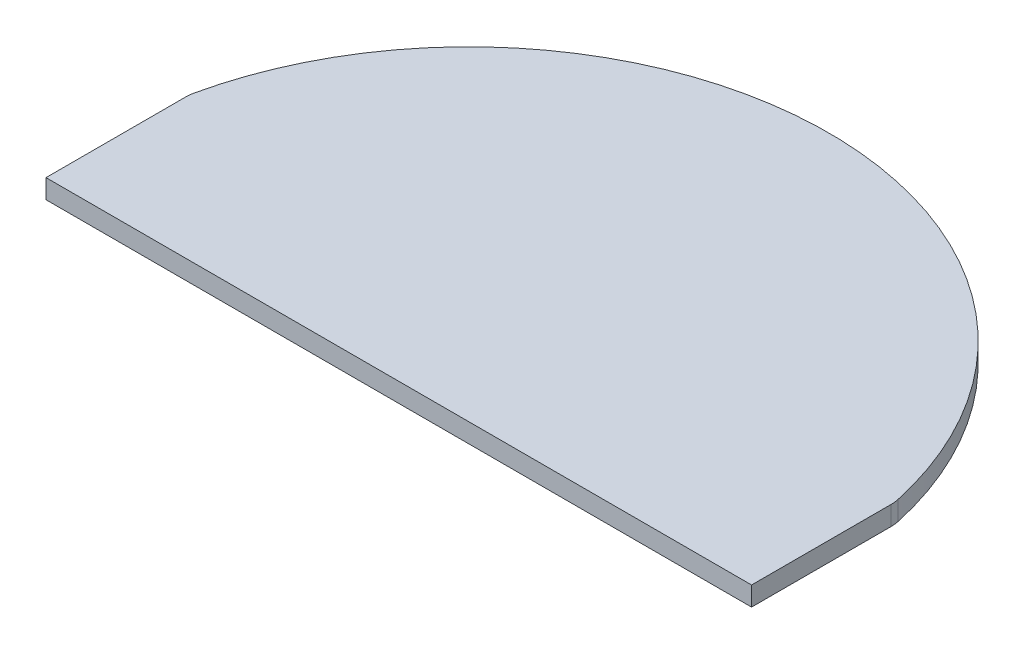
SolidWorks part; units mm, degrees
ref_plane "Front Plane" through (0, 0, 0) normal (0, 0, 1) x (1, 0, 0)
ref_plane "Top Plane" through (0, 0, 0) normal (0, 1, 0) x (1, 0, 0)
ref_plane "Right Plane" through (0, 0, 0) normal (1, 0, 0) x (0, 0, -1)
sketch "Sketch1" plane through (0, 0, 0) normal (0, 1, 0) x (1, 0, 0)
  line L0 (0, 0) -> (250, 0)
  line L1 (0, 0) -> (0, 50.8)
  line L2 (250, 0) -> (250, 50.8)
  line L3 (0, 50.8) -> (0, 152.4) construction
  line L4 (0, 152.4) -> (311.8083, 152.4) construction
  arc A0 (0, 50.8) -> (250, 50.8) centre (125, 24.7053) cw
  dimension "D1" = 250
  dimension "D2" = 50.8
  dimension "D3" = 101.6
extrude "Boss-Extrude1" add sketch "Sketch1" along normal blind 6.8
fillet "Fillet1" radius 12.7 2 edges at (250, 3.4, -50.8) (0, 3.4, -50.8)
